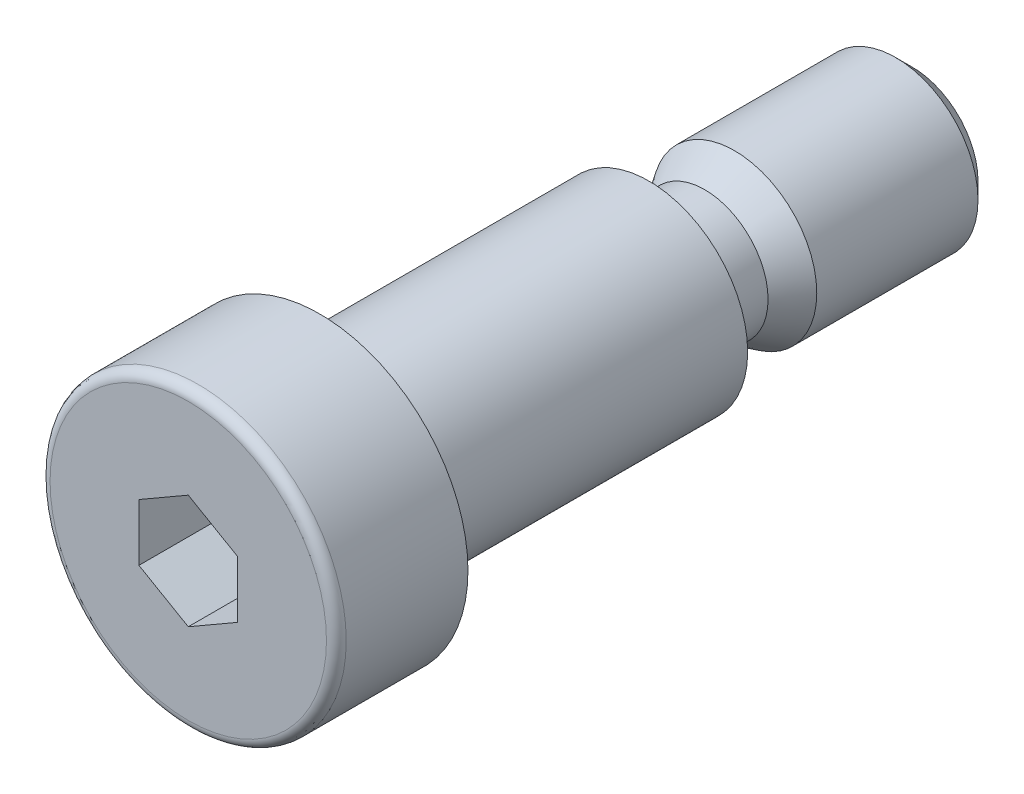
SolidWorks part; units mm, degrees
material "1.0545 (S355N)"
ref_plane "Płaszczyzna przednia" through (0, 0, 0) normal (0, 0, 1) x (1, 0, 0)
ref_plane "Płaszczyzna górna" through (0, 0, 0) normal (0, 1, 0) x (1, 0, 0)
ref_plane "Płaszczyzna prawa" through (0, 0, 0) normal (1, 0, 0) x (0, 0, -1)
sketch "Szkic1" plane through (0, 0, 0) normal (0, 1, 0) x (1, 0, 0)
  line L0 (5, 15.2) -> (3.85, 13.39)
  line L1 (9, -18) -> (-9, -18)
  line L2 (9, -18) -> (9, -10)
  line L3 (9, -10) -> (-9, -10)
  line L4 (-9, -18) -> (-9, -10)
  line L5 (6, -10) -> (-6, -10)
  line L6 (6, -10) -> (6, 10)
  line L7 (6, 10) -> (-6, 10)
  line L8 (-6, -10) -> (-6, 10)
  line L9 (-3.85, 10) -> (3.85, 10)
  line L10 (-3.85, 10) -> (-3.85, 13.39)
  line L11 (-3.85, 13.39) -> (3.85, 13.39)
  line L12 (3.85, 10) -> (3.85, 13.39)
  line L13 (5, 15.2) -> (5, 25)
  line L14 (5, 25) -> (4, 26)
  line L15 (4, 26) -> (-4, 26)
  line L16 (-4, 26) -> (-5, 25)
  line L17 (-5, 25) -> (-5, 15.2)
  line L18 (-5, 15.2) -> (-3.85, 13.39)
  line L19 (5, 15.2) -> (-5, 15.2) construction
  line L20 (5, 25) -> (-5, 25) construction
  line L21 (0, -19.9356) -> (0, 25.6583) construction
  line L22 (0, -18) -> (0, 26)
  point P4 (0, -10)
  point P14 (0, -10)
  point P15 (0, 10)
  point P16 (0, 10)
  point P17 (-6, 0)
  point P23 (0, 15.2)
  point P25 (0, 26)
  point P26 (0, 13.39)
  point P27 (0, 25)
  dimension "D1" = 18
  dimension "D2" = 8
  dimension "D3" = 12
  dimension "l1" = 20
  dimension "D5" = 7.7
  dimension "D6" = 16
  dimension "D7" = 10
  dimension "D8" = 8
  dimension "D9" = 1
  dimension "D10" = 1.81
  dimension "D11" = 9.8
revolve "Obrót1" add sketch "Szkic1" angle 360 about L22
sketch "Szkic2" plane through (0, 0, 18) normal (0, 0, 1) x (1, 0, 0)
  line L1 (3, 1.7321) -> (0, 3.4641)
  line L2 (0, 3.4641) -> (-3, 1.7321)
  line L3 (-3, 1.7321) -> (-3, -1.7321)
  line L4 (-3, -1.7321) -> (0, -3.4641)
  line L5 (0, -3.4641) -> (3, -1.7321)
  line L6 (3, -1.7321) -> (3, 1.7321)
  circle A0 centre (0, 0) radius 3 construction
  dimension "D1" = 6
extrude "Wytnij-wyciągnięcie1" cut sketch "Szkic2" against normal blind 4.9
fillet "Zaokrąglenie1" radius 0.6 1 edges at (9, 0, 18)
